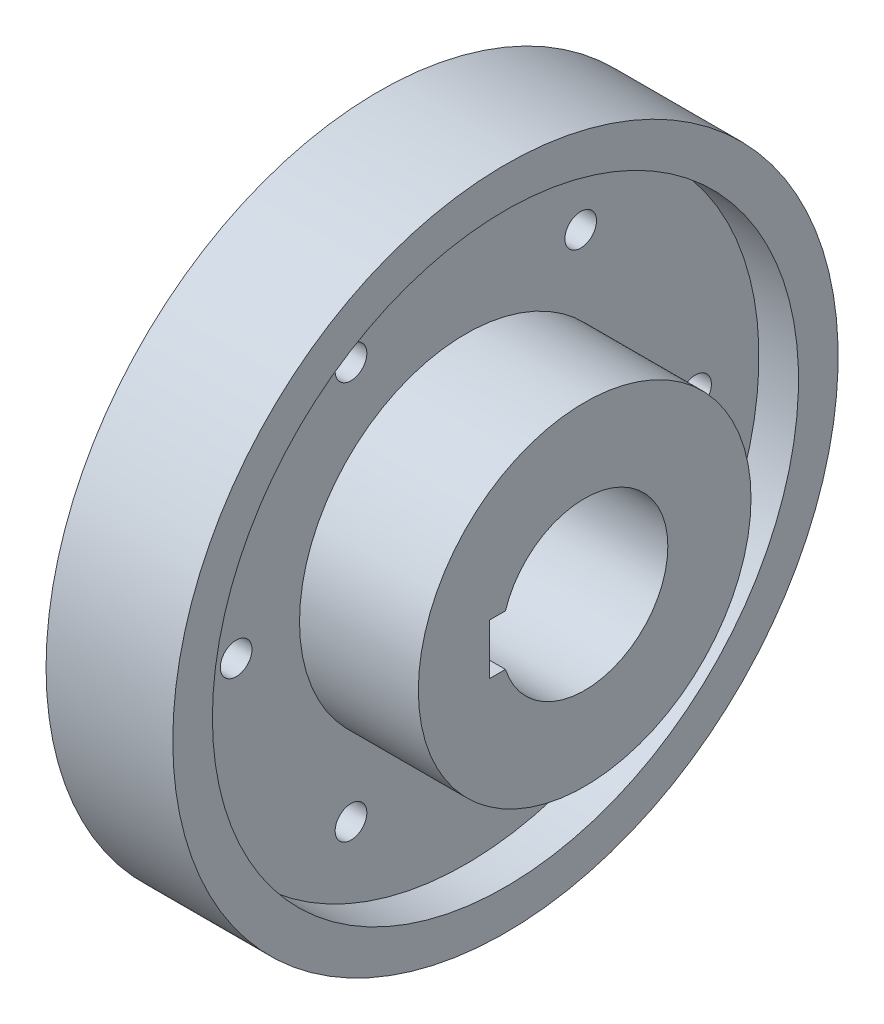
SolidWorks part; units mm, degrees
material "Malleable Cast Iron"
ref_plane "Front Plane" through (0, 0, 0) normal (1, 0, 0) x (0, 1, 0)
ref_plane "Top Plane" through (0, 0, 0) normal (0, 0, 1) x (0, 1, 0)
ref_plane "Right Plane" through (0, 0, 0) normal (0, 1, 0) x (-1, 0, 0)
sketch "Sketch2" plane through (0, 0, 0) normal (0, 1, 0) x (-1, 0, 0)
  line L0 (-138.4348, 52.5) -> (-268.4348, 52.5)
  line L1 (-268.4348, 52.5) -> (-268.4348, 105)
  line L2 (-268.4348, 105) -> (-193.4348, 105)
  line L3 (-193.4348, 105) -> (-193.4348, 185)
  line L4 (-193.4348, 185) -> (-218.4348, 185)
  line L5 (-218.4348, 185) -> (-218.4348, 210)
  line L6 (-218.4348, 210) -> (-138.4348, 210)
  line L7 (-138.4348, 210) -> (-138.4348, 52.5)
  line L8 (0, 0) -> (-419.8736, 0) construction
  dimension "D1" = 105
  dimension "D2" = 25
  dimension "D3" = 210
  dimension "D4" = 55
  dimension "D5" = 80
  dimension "D6" = 50
  dimension "D7" = 52.5
revolve "Revolve1" add sketch "Sketch2" angle 360 about L8
sketch "Sketch3" plane through (193.4348, 0, 0) normal (1, 0, 0) x (0, 1, 0)
  circle A0 centre (0, 0) radius 145 construction
  circle A1 centre (0, 145) radius 10
  dimension "D1" = 290
  dimension "D2" = 20
extrude "Cut-Extrude1" cut sketch "Sketch3" against normal through all
pattern_circular "CirPattern1" count 6 over 360 about axis through (0, 0, 0) along (1, 0, 0) of "Cut-Extrude1"
sketch "Sketch4" plane through (138.4348, 0, 0) normal (-1, 0, 0) x (0, -1, 0)
  line L1 (-16, 60.0025) -> (16, 60.0025)
  line L2 (-16, 60.0025) -> (-16, 50.0025)
  line L3 (-16, 50.0025) -> (16, 50.0025)
  line L4 (16, 60.0025) -> (16, 50.0025)
  line L5 (-16, 60.0025) -> (16, 50.0025) construction
  line L6 (-16, 50.0025) -> (16, 60.0025) construction
  circle A0 centre (0, 0) radius 52.5 construction
  point P0 (0, 55.0025)
  point P7 (0, 0)
  dimension "D1" = 10
  dimension "D2" = 32
extrude "Cut-Extrude2" cut sketch "Sketch4" against normal through all both and the other way through all
sketch "Sketch5" plane through (138.4348, 0, 0) normal (-1, 0, 0) x (0, -1, 0)
  circle A0 centre (0, 0) radius 100
  dimension "D1" = 200
extrude "Cut-Extrude3" cut sketch "Sketch5" against normal blind 10 and the other way through all
